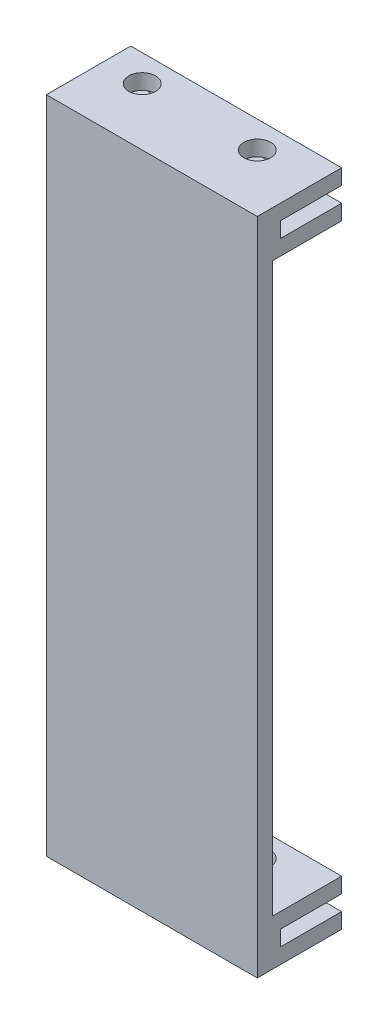
SolidWorks part; units mm, degrees
material "PET"
ref_plane "前视基准面" through (0, 0, 0) normal (0, 0, 1) x (1, 0, 0)
ref_plane "上视基准面" through (0, 0, 0) normal (0, 1, 0) x (1, 0, 0)
ref_plane "右视基准面" through (0, 0, 0) normal (1, 0, 0) x (0, 0, -1)
other "Configuration Table"
sketch "草图1" plane through (0, 0, 0) normal (0, 1, 0) x (1, 0, 0)
  line L1 (-15, 5.5) -> (15, 5.5)
  line L2 (-15, 5.5) -> (-15, -5.5)
  line L3 (-15, -5.5) -> (15, -5.5)
  line L4 (15, 5.5) -> (15, -5.5)
  line L5 (-15, 5.5) -> (15, -5.5) construction
  line L6 (-15, -5.5) -> (15, 5.5) construction
  point P0 (0, 0)
  dimension "D1" = 30
  dimension "D2" = 11
extrude "凸台-拉伸1" add sketch "草图1" along normal blind 6
sketch "草图2" plane through (-15, 0, 0) normal (-1, 0, 0) x (0, 0, 1)
  line L0 (-5.5, 6) -> (-5.5, 0) construction
  line L1 (-13.5, 2) -> (2.5, 2)
  line L2 (-13.5, 2) -> (-13.5, 4)
  line L3 (-13.5, 4) -> (2.5, 4)
  line L4 (2.5, 2) -> (2.5, 4)
  line L5 (-13.5, 2) -> (2.5, 4) construction
  line L6 (-13.5, 4) -> (2.5, 2) construction
  line L7 (-5.5, 6) -> (5.5, 6) construction
  line L8 (5.5, 6) -> (5.5, 0) construction
  point P0 (-5.5, 3)
  dimension "D1" = 2
  dimension "D2" = 3
extrude "切除-拉伸1" cut sketch "草图2" against normal blind 144
sketch "草图3" plane through (0, 6, 0) normal (0, 1, 0) x (1, 0, 0)
  line L0 (2, 5.5) -> (-2, 5.5)
  line L1 (15, 5.5) -> (-15, 5.5) construction
  line L2 (-2, 5.5) -> (-2, -3.5)
  line L3 (-2, -3.5) -> (-15, -3.5)
  line L4 (-15, 5.5) -> (-15, -5.5) construction
  line L5 (-15, -3.5) -> (-15, -5.5)
  line L6 (-15, -5.5) -> (15, -5.5)
  line L7 (-15, -5.5) -> (15, -5.5) construction
  line L8 (0, 5.5) -> (0, -5.5) construction
  line L9 (15, -3.5) -> (15, -5.5)
  line L10 (2, -3.5) -> (15, -3.5)
  line L11 (2, 5.5) -> (2, -3.5)
  dimension "D1" = 2
  dimension "D2" = 2
extrude "凸台-拉伸2" add sketch "草图3" along normal blind 74
sketch "草图4" plane through (0, 6, 0) normal (0, 1, 0) x (1, 0, 0)
  line L0 (-15, 5.5) -> (-15, 2) construction
  line L1 (-15, 5.5) -> (-15, -3.5) construction
  line L2 (-15, 2) -> (15, 2) construction
  line L3 (15, -3.5) -> (15, 5.5) construction
  line L4 (0, 5.5) -> (0, -5.5) construction
  line L5 (2, 5.5) -> (-2, 5.5) construction
  line L6 (-15, -5.5) -> (15, -5.5) construction
  circle A0 centre (-7.5, 2) radius 1.75
  circle A1 centre (7.5, 2) radius 1.75
  point P10 (0, 2)
  dimension "D2" = 7.5
  dimension "D3" = 3.5
  dimension "D1" = 3.5
extrude "切除-拉伸2" cut sketch "草图4" against normal blind 144
sketch "草图5" plane through (-15, 0, 0) normal (-1, 0, 0) x (0, 0, 1)
  line L1 (-5.5, 0) -> (5.5, 0)
  line L2 (-5.5, 0) -> (-5.5, 80)
  line L3 (-5.5, 80) -> (5.5, 80)
  line L4 (5.5, 0) -> (5.5, 80)
extrude "切除-拉伸3" cut sketch "草图5" against normal blind 2.5
sketch "草图6" plane through (0, 6, 0) normal (0, 1, 0) x (1, 0, 0)
  line L0 (-12.5, -2.5) -> (-12.5, 7.5) construction
  line L1 (-22.5, 7.5) -> (-25.5, 7.5)
  line L2 (-12.5, -2.5) -> (-12.5, -5.5)
  arc A0 (-22.5, 7.5) -> (-12.5, -2.5) centre (-12.5, 7.5) ccw
  arc A1 (-25.5, 7.5) -> (-12.5, -5.5) centre (-12.5, 7.5) ccw
  dimension "D1" = 10
sketch "草图7" plane through (0, 80, 0) normal (0, 1, 0) x (1, 0, 0)
  line L1 (-2, 5.5) -> (2, 5.5)
  line L2 (-2, 5.5) -> (-2, -3.5)
  line L3 (-2, -3.5) -> (2, -3.5)
  line L4 (2, 5.5) -> (2, -3.5)
extrude "切除-拉伸4" cut sketch "草图7" against normal up to surface (74 mm away) up to face at (-7.25, 6, -1)
ref_plane "基准面1" through (0, 43, 0) normal (0, 1, 0) x (1, 0, 0)
mirror "镜向1" about plane through (0, 43, 0) normal (0, 1, 0) of "切除-拉伸3", "切除-拉伸2", "切除-拉伸1", "凸台-拉伸1"
sketch "草图8" plane through (15, 0, 0) normal (1, 0, 0) x (0, 0, -1)
  line L0 (-5.5, 86) -> (5.5, 86) construction
  line L1 (-5.5, 0) -> (-2.5, 0)
  line L2 (-5.5, 0) -> (-5.5, 86)
  line L3 (-5.5, 86) -> (-2.5, 86)
  line L4 (-2.5, 0) -> (-2.5, 86)
  line L5 (-2.5, 84) -> (-2.5, 82) construction
  dimension "D1" = 0
sketch "草图9" plane through (0, 0, 5.5) normal (0, 0, 1) x (1, 0, 0)
  line L0 (5.75, 6) -> (5.75, 80) construction
  text T0 "BACK" font "汉仪长仿宋体" height 8
